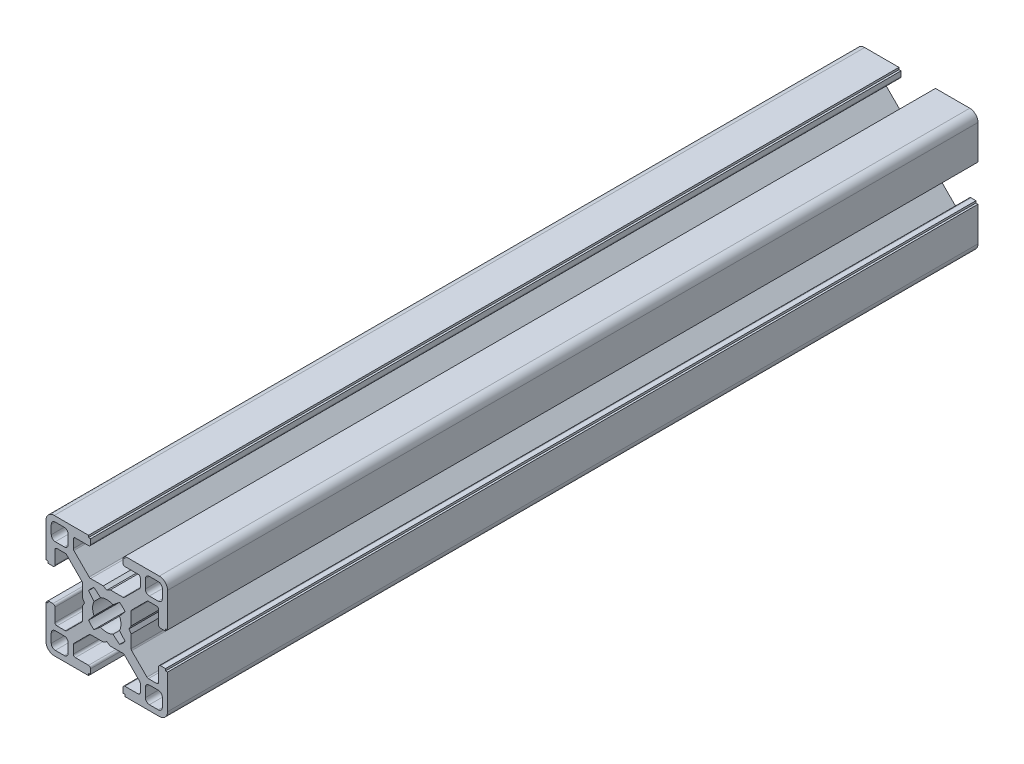
SolidWorks part; units mm, degrees
ref_plane "Front Plane" through (0, 0, 0) normal (0, 0, 1) x (1, 0, 0)
ref_plane "Top Plane" through (0, 0, 0) normal (0, 1, 0) x (1, 0, 0)
ref_plane "Right Plane" through (0, 0, 0) normal (1, 0, 0) x (0, 0, -1)
sketch "Sketch1" plane through (0, 0, 0) normal (0, 0, 1) x (1, 0, 0)
  line L0 (-15, 0) -> (15, 0) construction
  line L1 (0, -15) -> (0, 15) construction
  line L2 (-4.5, 15) -> (4.5, 15) construction
  line L3 (-4, -15) -> (4, -15) construction
  line L4 (-4.5, 15) -> (-4.5, 14.5)
  line L5 (-4.5, 14.5) -> (-4, 14.5)
  line L6 (-4, 14.5) -> (-4, 13.29)
  line L7 (-4.5, 12.79) -> (-7.7675, 12.79)
  line L8 (-8.2675, 12.29) -> (-8.2675, 10.2707)
  line L9 (-8.1211, 9.9171) -> (-4.3504, 6.1464)
  line L10 (-3.9968, 6) -> (0, 6)
  line L11 (0, 0) -> (-15, 15) construction
  line L12 (-4.5, 15) -> (-12.968, 15)
  line L14 (-12.705, 9.5135) -> (-10.5135, 9.5135)
  line L15 (-13.705, 10.5135) -> (-13.705, 12.705)
  line L16 (-12.705, 13.705) -> (-10.5135, 13.705)
  line L17 (-9.5135, 10.5135) -> (-9.5135, 12.705)
  line L18 (-13.705, 9.5135) -> (-9.5135, 13.705) construction
  line L19 (-13.705, 13.705) -> (-9.5135, 9.5135) construction
  line L20 (-3.1568, 4.5038) -> (-1.5303, 3.1477) construction
  line L21 (-4.5038, 3.1568) -> (-3.1477, 1.5303) construction
  line L22 (-6, 3.9968) -> (-6, 0)
  line L23 (-9.9171, 8.1211) -> (-6.1464, 4.3504)
  line L24 (-15, 4.5) -> (-15, 12.968)
  line L25 (-12.29, 8.2675) -> (-10.2707, 8.2675)
  line L26 (-12.79, 4.5) -> (-12.79, 7.7675)
  line L27 (-14.5, 4) -> (-13.29, 4)
  line L28 (-14.5, 4.5) -> (-14.5, 4)
  line L29 (-15, 4.5) -> (-14.5, 4.5)
  circle A0 centre (0, 0) radius 3.5
  arc A1 (-12.968, 15) -> (-15, 12.968) centre (-12.968, 12.968) ccw
  circle A2 centre (0, 0) radius 5.5 construction
  arc A3 (-10.5135, 9.5135) -> (-9.5135, 10.5135) centre (-10.5135, 10.5135) ccw
  arc A4 (-13.705, 12.705) -> (-12.705, 13.705) centre (-12.705, 12.705) cw
  arc A5 (-10.5135, 13.705) -> (-9.5135, 12.705) centre (-10.5135, 12.705) cw
  arc A6 (-12.705, 9.5135) -> (-13.705, 10.5135) centre (-12.705, 10.5135) cw
  arc A7 (-12.79, 4.5) -> (-13.29, 4) centre (-13.29, 4.5) cw
  arc A8 (-12.29, 8.2675) -> (-12.79, 7.7675) centre (-12.29, 7.7675) ccw
  arc A9 (-9.9171, 8.1211) -> (-10.2707, 8.2675) centre (-10.2707, 7.7675) ccw
  arc A10 (-6, 3.9968) -> (-6.1464, 4.3504) centre (-6.5, 3.9968) ccw
  arc A11 (-4.3504, 6.1464) -> (-3.9968, 6) centre (-3.9968, 6.5) ccw
  arc A12 (-4, 13.29) -> (-4.5, 12.79) centre (-4.5, 13.29) cw
  arc A13 (-7.7675, 12.79) -> (-8.2675, 12.29) centre (-7.7675, 12.29) ccw
  arc A14 (-8.2675, 10.2707) -> (-8.1211, 9.9171) centre (-7.7675, 10.2707) ccw
  point P4 (0, 0)
  point P8 (0, 0)
  point P13 (0, 15)
  point P15 (0, -15)
  point P16 (0, 6)
  point P23 (-11.6092, 11.6093)
  point P26 (0, 6)
  point P62 (-12.79, 4)
  point P65 (-12.79, 8.2675)
  point P68 (-10.0636, 8.2675)
  point P71 (-6, 4.2039)
  point P74 (-4.2039, 6)
  point P77 (-4, 12.79)
  point P80 (-8.2675, 12.79)
  point P83 (-8.2675, 10.0636)
  dimension "Center Hole Diameter" = 7
  dimension "D11" = 2.032
  dimension "D9" = 11
  dimension "D13" = 1
  dimension "D14" = 0.5
  dimension "Rail Height" = 30
  dimension "Rail Width" = 30
  dimension "T-Slot Width" = 8
  dimension "T-Slot Depth" = 9
  dimension "D1" = 9
  dimension "D2" = 45
  dimension "D3" = 8
  dimension "D4" = 2.21
  dimension "D5" = 16.535
  dimension "D7" = 2.54
  dimension "D6" = 1.295
  dimension "D8" = 1.246
  dimension "D10" = 10.36
  dimension "D12" = 1.905
sketch "Sketch2" plane through (0, 0, 0) normal (1, 0, 0) x (0, 0, -1)
  line L0 (-76.2, 0) -> (76.2, 0) construction
  line L2 (0, -15) -> (0, 15) construction
  line L3 (0, -15) -> (0, 15) construction
  line L4 (-76.2, -15) -> (-76.2, 15) construction
  line L5 (76.2, -15) -> (76.2, 15) construction
  point P0 (-38.7, 0)
  point P3 (0, 0)
  point P4 (38.7, 0)
  point P12 (-76.2, 0)
  point P14 (76.2, 0)
  dimension "Length" = 152.4
  dimension "D1" = 37.5
sketch "Sketch3" plane through (0, 0, 0) normal (0, 0, 1) x (1, 0, 0)
  line L0 (-4.5038, 3.1568) -> (-3.1477, 1.5303)
  line L1 (0, 3.5) -> (0, 5.5)
  line L2 (-5.5, 0) -> (-3.5, 0)
  line L7 (-6, 3.9968) -> (-6, 0) construction
  line L31 (-9.9171, 8.1211) -> (-6.1464, 4.3504) construction
  line L117 (-12.29, 8.2675) -> (-10.2707, 8.2675) construction
  line L118 (-12.79, 4.5) -> (-12.79, 7.7675) construction
  line L157 (-12.705, 9.5135) -> (-10.5135, 9.5135)
  line L158 (-9.5135, 10.5135) -> (-9.5135, 12.705)
  line L163 (-10.5135, 13.705) -> (-12.705, 13.705)
  line L164 (-13.705, 12.705) -> (-13.705, 10.5135)
  line L165 (-12.705, 9.5135) -> (-10.5135, 9.5135)
  line L166 (-9.5135, 10.5135) -> (-9.5135, 12.705)
  line L167 (-10.5135, 13.705) -> (-12.705, 13.705)
  line L168 (-13.705, 12.705) -> (-13.705, 10.5135)
  line L169 (-14.5, 4) -> (-13.29, 4) construction
  line L170 (-14.5, 4.5) -> (-14.5, 4) construction
  line L171 (-15, 4.5) -> (-14.5, 4.5) construction
  line L172 (-15, 4.5) -> (-15, 12.968) construction
  line L173 (-4.5, 15) -> (-12.968, 15) construction
  line L174 (-4.5, 15) -> (-4.5, 14.5) construction
  line L175 (-4.5, 14.5) -> (-4, 14.5) construction
  line L176 (-4, 14.5) -> (-4, 13.29) construction
  line L177 (-4.5, 12.79) -> (-7.7675, 12.79) construction
  line L178 (-8.2675, 12.29) -> (-8.2675, 10.2707) construction
  line L179 (-8.1211, 9.9171) -> (-4.3504, 6.1464) construction
  line L180 (-3.9968, 6) -> (0, 6) construction
  line L181 (-6, 3.9968) -> (-6, 0.866)
  line L182 (-9.9171, 8.1211) -> (-6.1464, 4.3504)
  line L183 (-12.29, 8.2675) -> (-10.2707, 8.2675)
  line L184 (-12.79, 4.5) -> (-12.79, 7.7675)
  line L185 (-14.5, 4) -> (-13.29, 4)
  line L186 (-14.5, 4.5) -> (-14.5, 4)
  line L187 (-15, 4.5) -> (-14.5, 4.5)
  line L188 (-15, 4.5) -> (-15, 12.968)
  line L189 (-4.5, 15) -> (-12.968, 15)
  line L190 (-4.5, 15) -> (-4.5, 14.5)
  line L191 (-4.5, 14.5) -> (-4, 14.5)
  line L192 (-4, 14.5) -> (-4, 13.29)
  line L193 (-4.5, 12.79) -> (-7.7675, 12.79)
  line L194 (-8.2675, 12.29) -> (-8.2675, 10.2707)
  line L195 (-8.1211, 9.9171) -> (-4.3504, 6.1464)
  line L196 (-3.9968, 6) -> (-0.866, 6)
  line L197 (-0.866, 6) -> (0, 5.5)
  line L198 (0, -15) -> (0, 15) construction
  line L199 (0, 0) -> (-15, 15) construction
  line L200 (0, 0) -> (-15, 15) construction
  line L201 (-3.1568, 4.5038) -> (-1.5303, 3.1477) construction
  line L202 (-3.1568, 4.5038) -> (-1.5303, 3.1477)
  line L203 (-6, 0.866) -> (-5.5, 0)
  line L204 (-15, 0) -> (15, 0) construction
  line L205 (-15, 0) -> (15, 0) construction
  line L206 (0, -15) -> (0, 15) construction
  arc A0 (-3.5, 0) -> (-3.1477, 1.5303) centre (0, 0) cw
  arc A10 (-6, 3.9968) -> (-6.1464, 4.3504) centre (-6.5, 3.9968) ccw construction
  circle A16 centre (0, 0) radius 3.5
  arc A18 (0, 3.5) -> (-1.5303, 3.1477) centre (0, 0) ccw
  arc A20 (-9.9171, 8.1211) -> (-10.2707, 8.2675) centre (-10.2707, 7.7675) ccw construction
  arc A22 (-12.29, 8.2675) -> (-12.79, 7.7675) centre (-12.29, 7.7675) ccw construction
  arc A28 (-13.29, 4) -> (-12.79, 4.5) centre (-13.29, 4.5) ccw construction
  arc A29 (-10.5135, 9.5135) -> (-9.5135, 10.5135) centre (-10.5135, 10.5135) ccw
  arc A30 (-9.5135, 12.705) -> (-10.5135, 13.705) centre (-10.5135, 12.705) ccw
  arc A31 (-12.705, 13.705) -> (-13.705, 12.705) centre (-12.705, 12.705) ccw
  arc A32 (-13.705, 10.5135) -> (-12.705, 9.5135) centre (-12.705, 10.5135) ccw
  arc A33 (-10.5135, 9.5135) -> (-9.5135, 10.5135) centre (-10.5135, 10.5135) ccw
  arc A34 (-9.5135, 12.705) -> (-10.5135, 13.705) centre (-10.5135, 12.705) ccw
  arc A35 (-12.705, 13.705) -> (-13.705, 12.705) centre (-12.705, 12.705) ccw
  arc A36 (-13.705, 10.5135) -> (-12.705, 9.5135) centre (-12.705, 10.5135) ccw
  arc A37 (-12.968, 15) -> (-15, 12.968) centre (-12.968, 12.968) ccw construction
  arc A38 (-4.5, 12.79) -> (-4, 13.29) centre (-4.5, 13.29) ccw construction
  arc A39 (-7.7675, 12.79) -> (-8.2675, 12.29) centre (-7.7675, 12.29) ccw construction
  arc A40 (-8.2675, 10.2707) -> (-8.1211, 9.9171) centre (-7.7675, 10.2707) ccw construction
  arc A41 (-4.3504, 6.1464) -> (-3.9968, 6) centre (-3.9968, 6.5) ccw construction
  arc A42 (-6, 3.9968) -> (-6.1464, 4.3504) centre (-6.5, 3.9968) ccw
  arc A43 (-9.9171, 8.1211) -> (-10.2707, 8.2675) centre (-10.2707, 7.7675) ccw
  arc A44 (-12.29, 8.2675) -> (-12.79, 7.7675) centre (-12.29, 7.7675) ccw
  arc A45 (-13.29, 4) -> (-12.79, 4.5) centre (-13.29, 4.5) ccw
  arc A46 (-12.968, 15) -> (-15, 12.968) centre (-12.968, 12.968) ccw
  arc A47 (-4.5, 12.79) -> (-4, 13.29) centre (-4.5, 13.29) ccw
  arc A48 (-7.7675, 12.79) -> (-8.2675, 12.29) centre (-7.7675, 12.29) ccw
  arc A49 (-8.2675, 10.2707) -> (-8.1211, 9.9171) centre (-7.7675, 10.2707) ccw
  arc A50 (-4.3504, 6.1464) -> (-3.9968, 6) centre (-3.9968, 6.5) ccw
  circle A51 centre (0, 0) radius 5.5 construction
  arc A52 (-3.1568, 4.5038) -> (-4.5038, 3.1568) centre (0, 0) ccw
  dimension "D3" = 60
  dimension "D4" = 60
  dimension "D1" = 0
  dimension "D2" = 0
extrude "Boss-Extrude1" add sketch "Sketch3" along normal mid plane 200
pattern_circular "CirPattern1" count 4 over 360 about axis through (0, 0, 0) along (0, 0, 1) of "Boss-Extrude1"
ref_plane "Contact Plane1" through (15, 0, 0) normal (1, 0, 0) x (0, 0, -1)
ref_plane "Contact Plane2" through (0, -15, 0) normal (0, 1, 0) x (1, 0, 0)
ref_plane "Contact Plane3" through (-15, 0, 0) normal (1, 0, 0) x (0, 0, -1)
ref_plane "Contact Plane4" through (0, 15, 0) normal (0, 1, 0) x (1, 0, 0)
equation "\"D1@Sketch2\" = \"Rail Height@Sketch1\" * 1.25"
equation "\"D1@Sketch1\"=\"T-Slot Width@Sketch1\"+1mm"
equation "\"D3@Sketch1\"= \"T-Slot Width@Sketch1\""
equation "\"D1@Boss-Extrude1\"=\"Length\""
equation "\"Length\"= 200"
